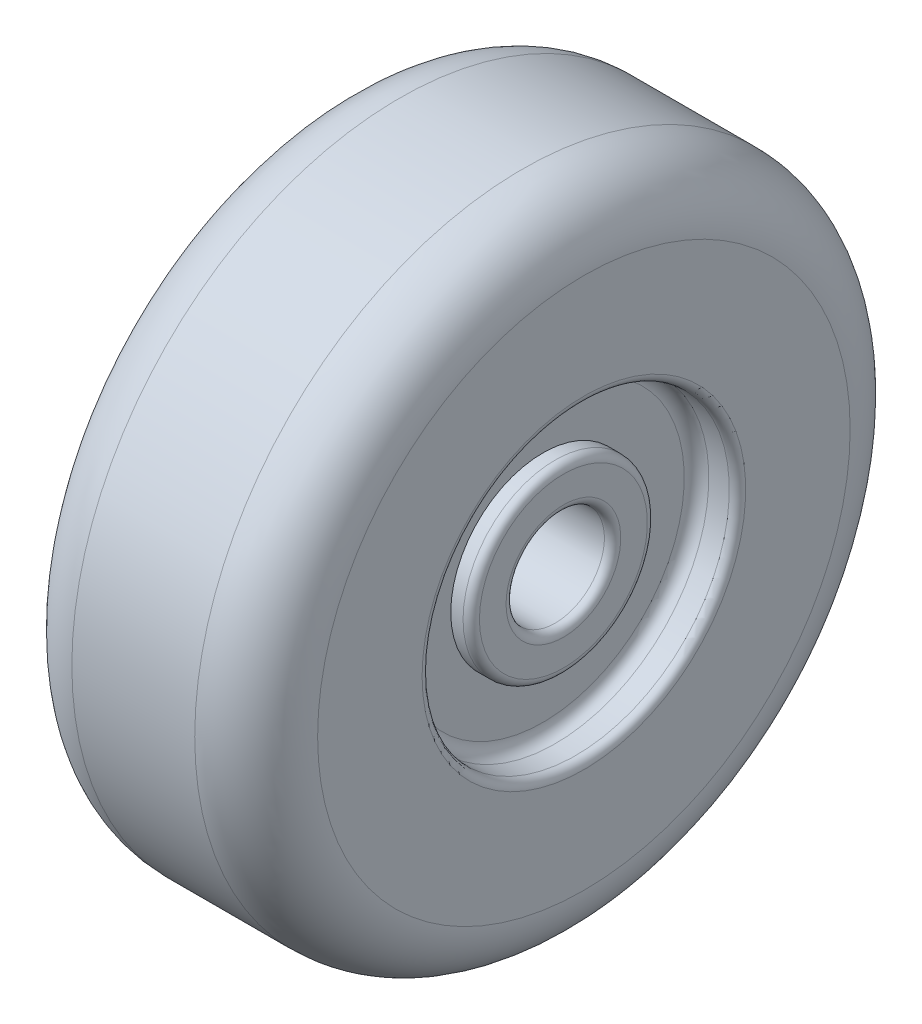
SolidWorks part; units mm, degrees
ref_plane "Plano frontal" through (0, 0, 0) normal (0, 0, 1) x (1, 0, 0)
ref_plane "Plano superior" through (0, 0, 0) normal (0, 1, 0) x (1, 0, 0)
ref_plane "Plano direito" through (0, 0, 0) normal (1, 0, 0) x (0, 0, -1)
sketch "Esboço1" plane through (0, 0, 0) normal (1, 0, 0) x (0, 0, -1)
  circle A6 centre (0, 0) radius 8
  circle A7 centre (0, 0) radius 4.75
  circle A8 centre (0, 0) radius 1.75
  dimension "D1" = 3.5
  dimension "D2" = 16
  dimension "D3" = 9.5
sketch "Esboço2" plane through (0, 0, 0) normal (0, 0, 1) x (1, 0, 0)
  line L0 (0, 0) -> (12.6911, 0) construction
  line L1 (0, 0) -> (0, 12.8674) construction
  line L2 (-2.3, 1.2) -> (2.3, 1.2)
  line L8 (-1.5, 8) -> (1.5, 8)
  line L9 (-2.3, 2.25) -> (-2, 2.25)
  line L11 (3, 6.5) -> (3, 3.95)
  line L14 (2.8, 3.75) -> (2.3, 3.75)
  line L15 (2, 3.45) -> (2, 2.25)
  line L17 (2.5, 1.4) -> (2.5, 2.05)
  line L18 (2.3, 2.25) -> (2, 2.25)
  line L19 (-2.5, 1.4) -> (-2.5, 2.05)
  line L21 (-2, 3.45) -> (-2, 2.25)
  line L22 (-2.8, 3.75) -> (-2.3, 3.75)
  line L25 (-3, 6.5) -> (-3, 3.95)
  arc A0 (2.3, 3.75) -> (2, 3.45) centre (2.3, 3.45) ccw
  arc A3 (2.5, 2.05) -> (2.3, 2.25) centre (2.3, 2.05) ccw
  arc A4 (1.5, 8) -> (3, 6.5) centre (1.5, 6.5) cw
  arc A5 (-1.5, 8) -> (-3, 6.5) centre (-1.5, 6.5) ccw
  arc A6 (-2.5, 2.05) -> (-2.3, 2.25) centre (-2.3, 2.05) cw
  arc A9 (-2.3, 3.75) -> (-2, 3.45) centre (-2.3, 3.45) cw
  arc A10 (2.5, 1.4) -> (2.3, 1.2) centre (2.3, 1.4) cw
  arc A11 (-2.5, 1.4) -> (-2.3, 1.2) centre (-2.3, 1.4) ccw
  arc A12 (3, 3.95) -> (2.8, 3.75) centre (2.8, 3.95) cw
  arc A13 (-3, 3.95) -> (-2.8, 3.75) centre (-2.8, 3.95) ccw
  point P3 (0, 1.75)
  point P5 (0, 4.75)
  point P6 (0, 8)
  point P9 (0, 8)
  point P13 (-3, 8)
  point P23 (3.5, 3.75)
  point P26 (3.5, 4.75)
  point P32 (2.5, 2.25)
  point P34 (3, 8)
  point P54 (0, 1.75)
  point P55 (-2.5, 2.25)
  point P56 (-3.5, 4.75)
  point P57 (-3.5, 3.75)
  dimension "D5" = 0.3
  dimension "D8" = 0.2
  dimension "D9" = 1.5
  dimension "D6" = 0.2
  dimension "D2" = 0.2
  dimension "D1" = 3
  dimension "D3" = 1
  dimension "D4" = 2
  dimension "D10" = 1.2
revolve "Revolução1" add sketch "Esboço2" angle 360 about L0
